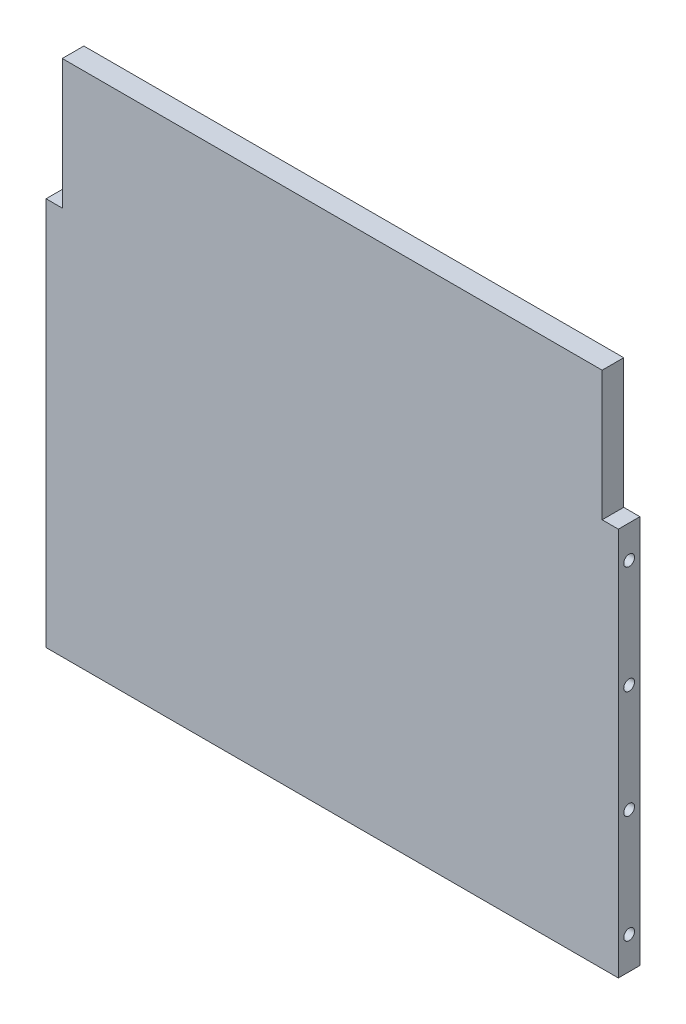
SolidWorks part; units mm, degrees
ref_plane "Front Plane" through (0, 0, 0) normal (0, 0, 1) x (1, 0, 0)
ref_plane "Top Plane" through (0, 0, 0) normal (0, 1, 0) x (1, 0, 0)
ref_plane "Right Plane" through (0, 0, 0) normal (1, 0, 0) x (0, 0, -1)
sketch "Sketch1" plane through (0, 0, 0) normal (0, 0, 1) x (1, 0, 0)
  line L1 (-250, 240) -> (250, 240)
  line L2 (-265, 120) -> (-265, -240)
  line L3 (-265, -240) -> (265, -240)
  line L4 (265, 120) -> (265, -240)
  line L5 (-250, 226.4151) -> (265, -240) construction
  line L6 (-265, -240) -> (250, 226.4151) construction
  line L9 (-265, 120) -> (-250, 120)
  line L10 (-250, 240) -> (-250, 120)
  line L13 (265, 120) -> (250, 120)
  line L14 (250, 240) -> (250, 120)
  point P0 (0, 0)
  dimension "D1" = 530
  dimension "D2" = 500
  dimension "D3" = 120
  dimension "D4" = 15
  dimension "D5" = 120
  dimension "D6" = 15
extrude "Boss-Extrude1" add sketch "Sketch1" along normal blind 20
sketch "Sketch3" plane through (265, 0, 0) normal (1, 0, 0) x (0, 0, -1)
  line L0 (-20, -240) -> (0, -240) construction
  line L1 (0, -240) -> (0, 120) construction
  line L2 (-20, 120) -> (0, 120) construction
  circle A0 centre (-10, -210) radius 5
  circle A1 centre (-10, -110) radius 5
  circle A2 centre (-10, -10) radius 5
  circle A3 centre (-10, 90) radius 5
  dimension "D1" = 30
  dimension "D3" = 10
  dimension "D4" = 100
  dimension "D5" = 100
  dimension "D6" = 100
  dimension "D2" = 10
  dimension "D7" = 30
extrude "Cut-Extrude1" cut sketch "Sketch3" against normal blind 30
sketch "Sketch4" plane through (-265, 0, 0) normal (-1, 0, 0) x (0, 0, 1)
  line L0 (20, -240) -> (0, -240) construction
  line L1 (20, 120) -> (0, 120) construction
  line L2 (0, 120) -> (0, -240) construction
  circle A0 centre (10, -210) radius 5
  circle A1 centre (10, -110) radius 5
  circle A2 centre (10, -10) radius 5
  circle A3 centre (10, 90) radius 5
  point P14 (0, 0)
  point P15 (0, 0)
  dimension "D1" = 30
  dimension "D3" = 100
  dimension "D4" = 100
  dimension "D5" = 100
  dimension "D2" = 10
  dimension "D6" = 30
extrude "Cut-Extrude2" cut sketch "Sketch4" against normal blind 30
